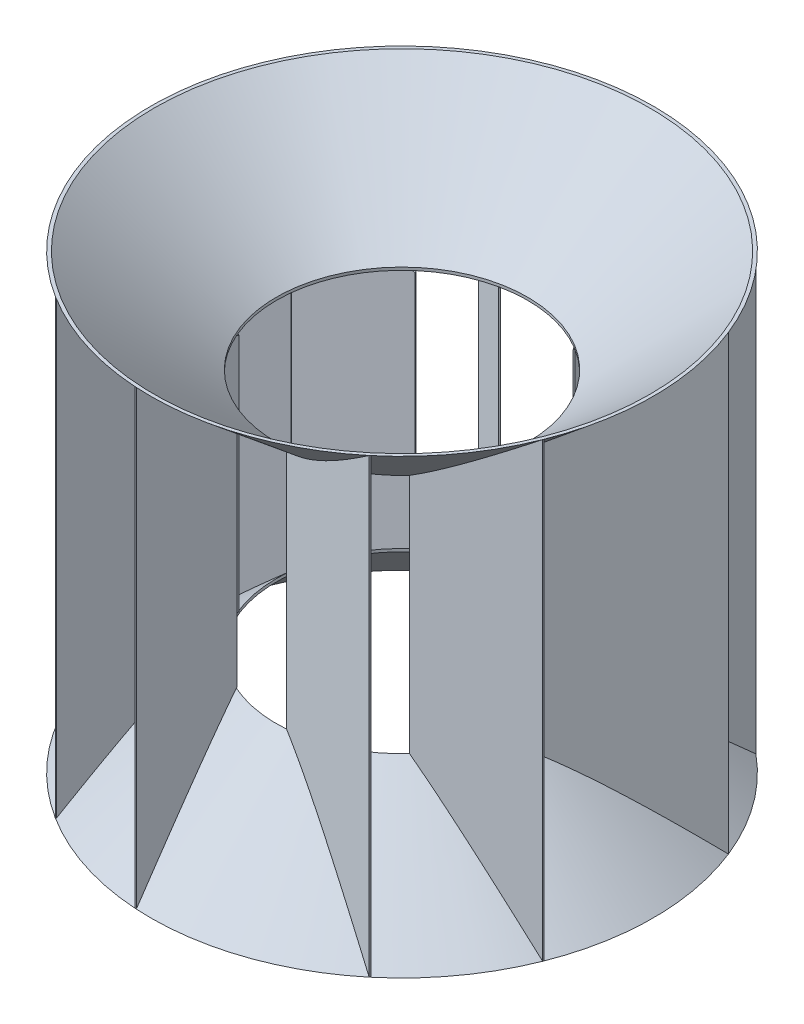
SolidWorks part; units mm, degrees
ref_plane "Alzado" through (0, 0, 0) normal (0, 0, 1) x (1, 0, 0)
ref_plane "Planta" through (0, 0, 0) normal (0, 1, 0) x (1, 0, 0)
ref_plane "Vista lateral" through (0, 0, 0) normal (1, 0, 0) x (0, 0, -1)
sketch "Croquis2" plane through (0, 0, 0) normal (0, 0, 1) x (1, 0, 0)
  line L0 (0, 0) -> (-290, 0) construction
  line L1 (-290, 0) -> (-580, 0) construction
  line L2 (-580, 0) -> (-290, 243.3389) construction
  line L3 (-290, 0) -> (-290, 243.3389) construction
  line L4 (-290, 243.3389) -> (0, 243.3389) construction
  line L5 (0, 243.3389) -> (0, 0) construction
  line L6 (-572.2214, 0) -> (-290, 236.8119)
  line L7 (-576.7861, -3.8302) -> (-286.7861, 239.5087) construction
  line L8 (-290, 236.8119) -> (-290, 243.3389)
  line L9 (-290, 243.3389) -> (-580, 0)
  line L10 (-580, 0) -> (-572.2214, 0)
  line L11 (0, 243.3389) -> (0, 799.3389) construction
  line L12 (0, 521.3389) -> (-97.1216, 521.3389) construction
  line L13 (-290, 799.3389) -> (-580, 1042.6778)
  line L14 (-290, 805.8659) -> (-290, 799.3389)
  line L15 (-572.2214, 1042.6778) -> (-290, 805.8659)
  line L16 (-580, 1042.6778) -> (-572.2214, 1042.6778)
  dimension "D1" = 290
  dimension "D2" = 290
  dimension "D3" = 40
  dimension "D5" = 556
  dimension "D4" = 5
revolve "Revolución1" add sketch "Croquis2" angle 360 about L11
ref_plane "Plano1" through (0, 459.825, 0) normal (0, 1, 0) x (1, 0, 0)
sketch "Croquis3" plane through (0, 459.825, 0) normal (0, 1, 0) x (1, 0, 0)
  line L0 (0, 0) -> (-850, 0) construction
  line L1 (-580, 0) -> (-580, 143.3288) construction
  line L2 (-580, 143.3288) -> (-562.0114, 143.3288) construction
  line L3 (-562.0114, 143.3288) -> (-562.0114, 243.3288) construction
  line L4 (-562.0114, 143.3288) -> (-562.0114, -143.3288) construction
  line L5 (-562.0114, 143.3288) -> (-188.1703, 220.6625)
  line L6 (-562.0114, -143.3288) -> (-288.0828, 33.2908)
  line L7 (-561.4037, 140.3909) -> (-187.5626, 217.7247)
  line L8 (-560.3858, -145.8501) -> (-286.4572, 30.7694)
  line L10 (-561.4037, 140.3909) -> (-562.0114, 143.3288)
  line L11 (-286.4572, 30.7694) -> (-288.0828, 33.2908)
  line L12 (-560.3858, -145.8501) -> (-562.0114, -143.3288)
  line L45 (-188.1703, 220.6625) -> (-187.5626, 217.7247)
  line L46 (151.7146, 247.1491) -> (149.1084, 245.6633)
  line L47 (-39.9636, 577.3099) -> (149.1084, 245.6633)
  line L48 (-39.9636, 577.3099) -> (-37.3573, 578.7957)
  line L49 (-37.3573, 578.7957) -> (151.7146, 247.1491)
  line L50 (-309.9848, 490.2136) -> (-57.3611, 284.2705)
  line L51 (-59.2567, 281.9452) -> (-57.3611, 284.2705)
  line L52 (-311.8804, 487.8884) -> (-59.2567, 281.9452)
  line L53 (-311.8804, 487.8884) -> (-309.9848, 490.2136)
  line L54 (281.9351, -67.9159) -> (279.7167, -65.8964)
  line L55 (536.7049, 216.4062) -> (279.7167, -65.8964)
  line L56 (536.7049, 216.4062) -> (538.9233, 214.3866)
  line L57 (538.9233, 214.3866) -> (281.9351, -67.9159)
  line L58 (370.4303, 446.2974) -> (252.6317, 142.398)
  line L59 (249.8345, 143.4823) -> (252.6317, 142.398)
  line L60 (367.6331, 447.3817) -> (249.8345, 143.4823)
  line L61 (367.6331, 447.3817) -> (370.4303, 446.2974)
  line L62 (22.5309, -289.1234) -> (23.766, -286.3895)
  line L63 (371.6654, -443.5635) -> (23.766, -286.3895)
  line L64 (371.6654, -443.5635) -> (370.4303, -446.2974)
  line L65 (370.4303, -446.2974) -> (22.5309, -289.1234)
  line L66 (538.9233, -214.3866) -> (213.4961, -196.2637)
  line L67 (213.6629, -193.2683) -> (213.4961, -196.2637)
  line L68 (539.0902, -211.3913) -> (213.6629, -193.2683)
  line L69 (539.0902, -211.3913) -> (538.9233, -214.3866)
  line L70 (-268.0103, -110.7722) -> (-265.0285, -111.102)
  line L71 (-307.003, -490.5435) -> (-265.0285, -111.102)
  line L72 (-307.003, -490.5435) -> (-309.9848, -490.2136)
  line L73 (-309.9848, -490.2136) -> (-268.0103, -110.7722)
  line L74 (-37.3573, -578.7957) -> (-120.6839, -263.6956)
  line L75 (-117.7836, -262.9287) -> (-120.6839, -263.6956)
  line L76 (-34.457, -578.0287) -> (-117.7836, -262.9287)
  line L77 (-34.457, -578.0287) -> (-37.3573, -578.7957)
  circle A0 centre (0, 0) radius 290 construction
  circle A1 centre (0, 0) radius 580 construction
  point P50 (0, 0)
  dimension "D1" = 580
  dimension "D2" = 1160
  dimension "D3" = 850
  dimension "D4" = 143.3288
  dimension "D5" = 100
  dimension "D6" = 78.313
  dimension "D7" = 57.188
  dimension "D10" = 5
  dimension "D8" = 3
  dimension "D9" = 3
extrude "Saliente-Extruir1" add sketch "Croquis3" along normal up to surface and the other way up to surface up to face at (290, 799.3389, 0) other way up to face at (580, 0, 0)
